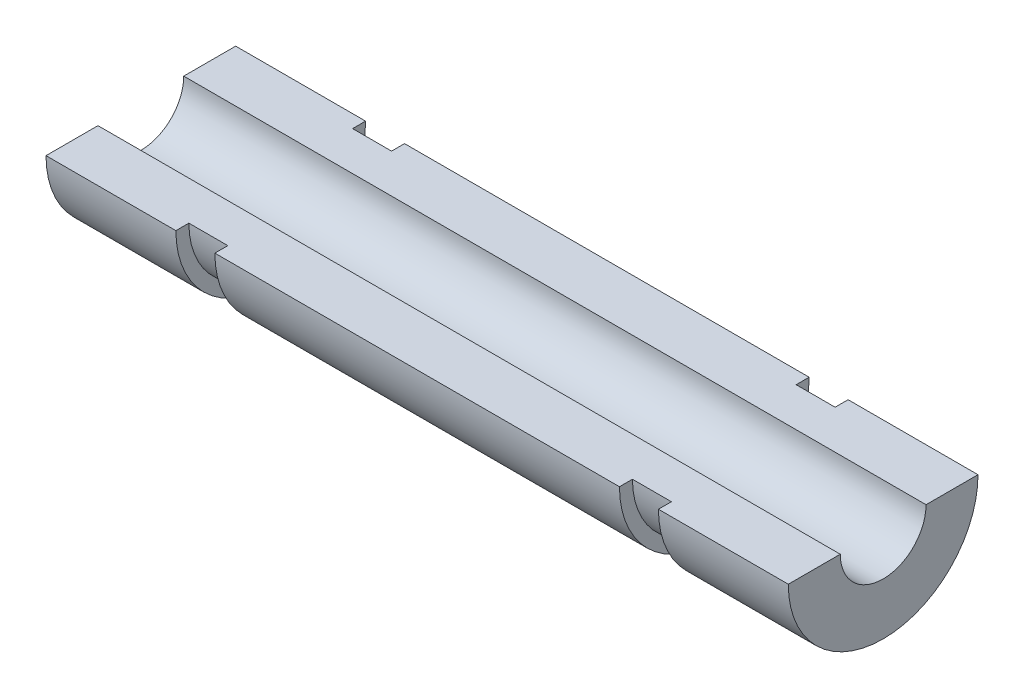
SolidWorks part; units mm, degrees
ref_plane "Front Plane" through (0, 0, 0) normal (0, 0, 1) x (1, 0, 0)
ref_plane "Top Plane" through (0, 0, 0) normal (0, 1, 0) x (1, 0, 0)
ref_plane "Right Plane" through (0, 0, 0) normal (1, 0, 0) x (0, 0, -1)
sketch "Sketch2" plane through (0, 0, 0) normal (0, 1, 0) x (1, 0, 0)
  line L0 (-28.575, 0) -> (28.575, 0) construction
  line L1 (-28.575, -3.302) -> (28.575, -3.302)
  line L2 (-28.575, -7.302) -> (-18.575, -7.302)
  line L3 (0, 0) -> (0, 18.0418) construction
  line L4 (18.575, -7.302) -> (28.575, -7.302)
  line L6 (18.575, -7.302) -> (18.575, -6.302)
  line L7 (18.575, -6.302) -> (15.575, -6.302)
  line L8 (15.575, -7.302) -> (15.575, -6.302)
  line L9 (-28.575, -7.302) -> (28.575, -7.302) construction
  line L10 (28.575, -7.302) -> (28.575, -3.302)
  line L11 (-28.575, -7.302) -> (-28.575, -3.302)
  line L12 (-15.575, -7.302) -> (-15.575, -6.302)
  line L13 (-18.575, -6.302) -> (-15.575, -6.302)
  line L14 (-18.575, -7.302) -> (-18.575, -6.302)
  line L15 (-15.575, -7.302) -> (15.575, -7.302)
  point P4 (0, 0)
  dimension "D1" = 57.15
  dimension "D2" = 3.302
  dimension "D4" = 10
  dimension "D5" = 3
  dimension "D6" = 1
  dimension "D3" = 4
revolve "Revolve1" add sketch "Sketch2" angle 180 about L0
